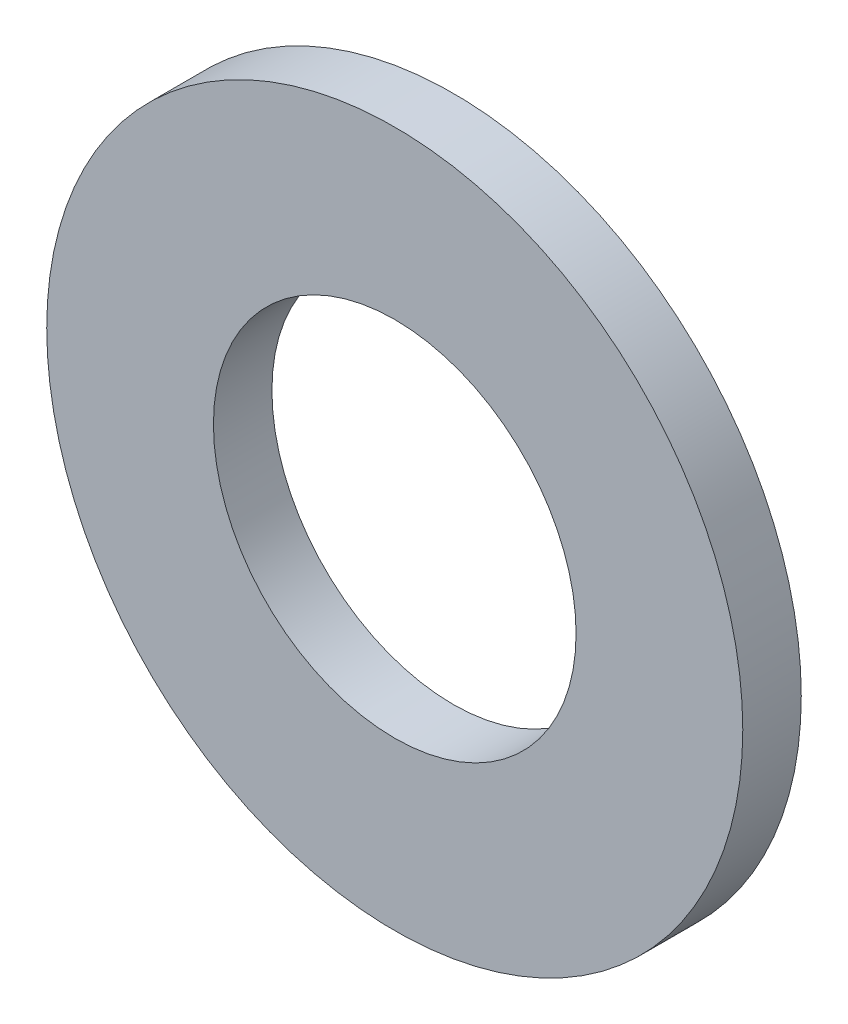
SolidWorks part; units mm, degrees
ref_plane "Plan de face" through (0, 0, 0) normal (0, 0, 1) x (1, 0, 0)
ref_plane "Plan de dessus" through (0, 0, 0) normal (0, 1, 0) x (1, 0, 0)
ref_plane "Plan de droite" through (0, 0, 0) normal (1, 0, 0) x (0, 0, -1)
sketch "Esquisse1" plane through (0, 0, 0) normal (0, 0, 1) x (1, 0, 0)
  circle A0 centre (0, 0) radius 5.95
  circle A1 centre (0, 0) radius 3.1
  dimension "D1" = 6.2
  dimension "D2" = 11.9
extrude "Boss.-Extru.1" add sketch "Esquisse1" along normal blind 1
